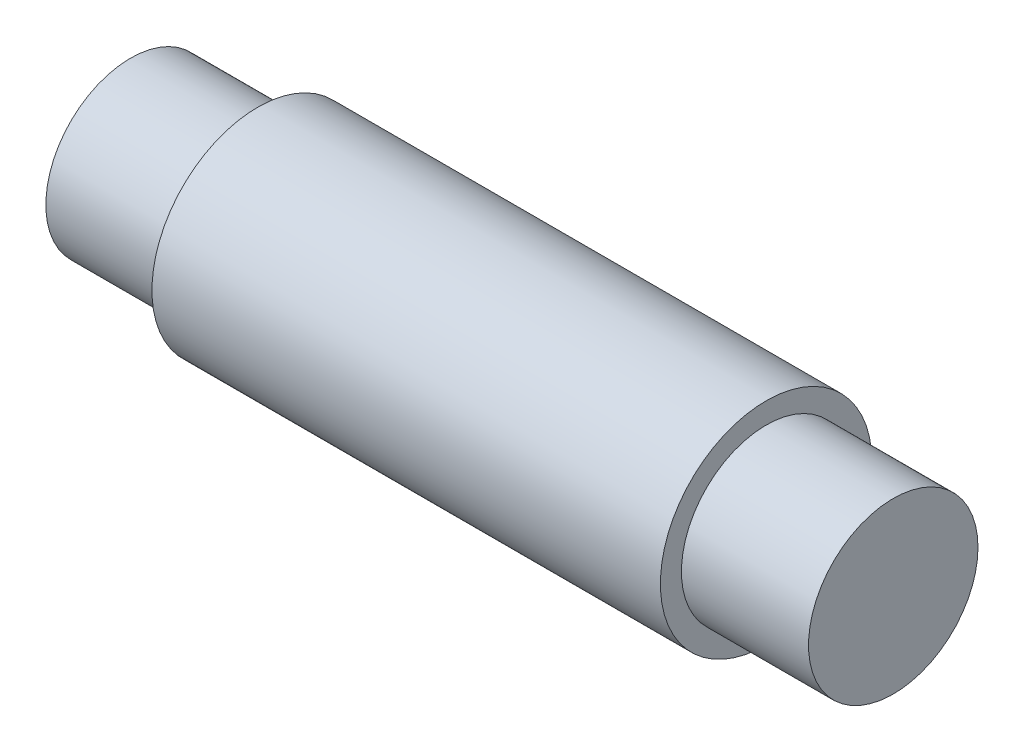
SolidWorks part; units mm, degrees
ref_plane "Front Plane" through (0, 0, 0) normal (0, 0, 1) x (1, 0, 0)
ref_plane "Top Plane" through (0, 0, 0) normal (0, 1, 0) x (1, 0, 0)
ref_plane "Right Plane" through (0, 0, 0) normal (1, 0, 0) x (0, 0, -1)
sketch "Sketch1" plane through (0, 0, 0) normal (0, 0, 1) x (1, 0, 0)
  line L0 (0, 0) -> (0, 50000) construction
  line L1 (1000, 0) -> (14.2875, 0) construction
  line L2 (0, 0) -> (0, 3.9624)
  line L3 (-9.525, 0) -> (9.525, 0)
  line L4 (-9.525, 3.9624) -> (9.525, 3.9624)
  line L5 (9.525, 0) -> (9.525, 3.9624)
  line L6 (9.525, 0) -> (9.525, 3.175)
  line L8 (9.525, 3.175) -> (14.2875, 3.175)
  line L9 (14.2875, 0) -> (14.2875, 3.175)
  line L10 (9.525, 0) -> (-9.525, 0) construction
  line L11 (-14.2875, 0) -> (-14.2875, 3.175)
  line L12 (-9.525, 3.175) -> (-14.2875, 3.175)
  line L13 (-9.525, 0) -> (-9.525, 3.9624)
  line L14 (-14.2875, 0) -> (-9.525, 0)
  line L15 (9.525, 0) -> (14.2875, 0)
  dimension "D1" = 9.525
  dimension "D2" = 28.575
  dimension "D3" = 3.9624
  dimension "D4" = 3.175
revolve "Revolve1" add sketch "Sketch1" angle 360 about L10
